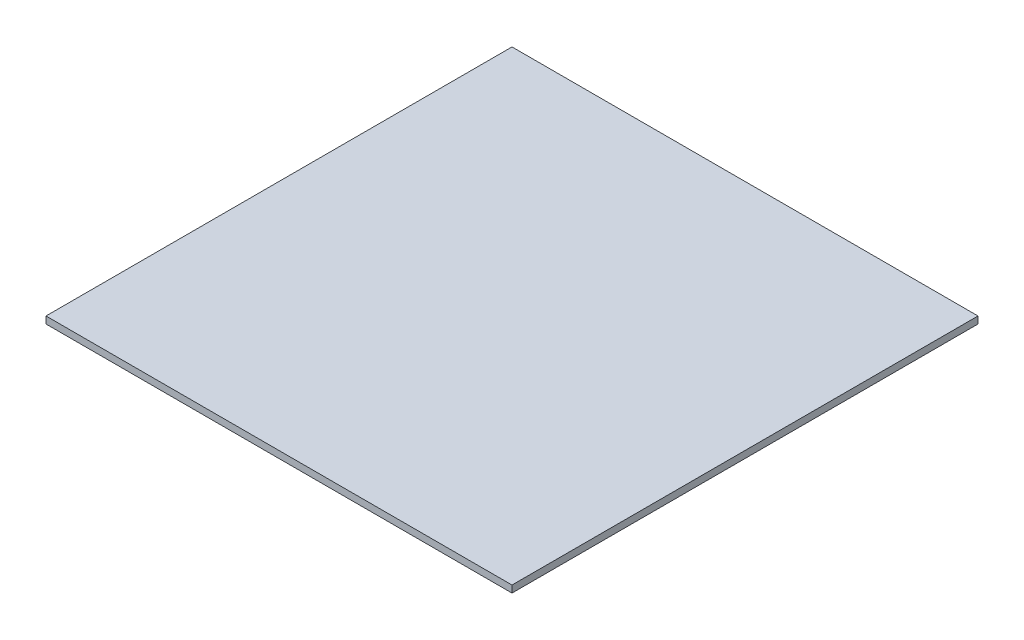
SolidWorks part; units mm, degrees
material "Concreto"
ref_plane "Plano frontal" through (0, 0, 0) normal (0, 0, 1) x (1, 0, 0)
ref_plane "Plano superior" through (0, 0, 0) normal (0, 1, 0) x (1, 0, 0)
ref_plane "Plano direito" through (0, 0, 0) normal (1, 0, 0) x (0, 0, -1)
sketch "Esboço1" plane through (0, 0, 0) normal (0, 1, 0) x (1, 0, 0)
  line L0 (-2000, 0) -> (2000, 0) construction
  line L1 (-2000, 2000) -> (2000, 2000)
  line L2 (-2000, 2000) -> (-2000, -2000)
  line L3 (-2000, -2000) -> (2000, -2000)
  line L4 (2000, 2000) -> (2000, -2000)
  line L5 (-2000, 2000) -> (2000, -2000) construction
  line L6 (-2000, -2000) -> (2000, 2000) construction
  point P0 (0, 0)
  dimension "D2" = 4000
extrude "Ressalto-extrusão1" add sketch "Esboço1" along normal blind 60
